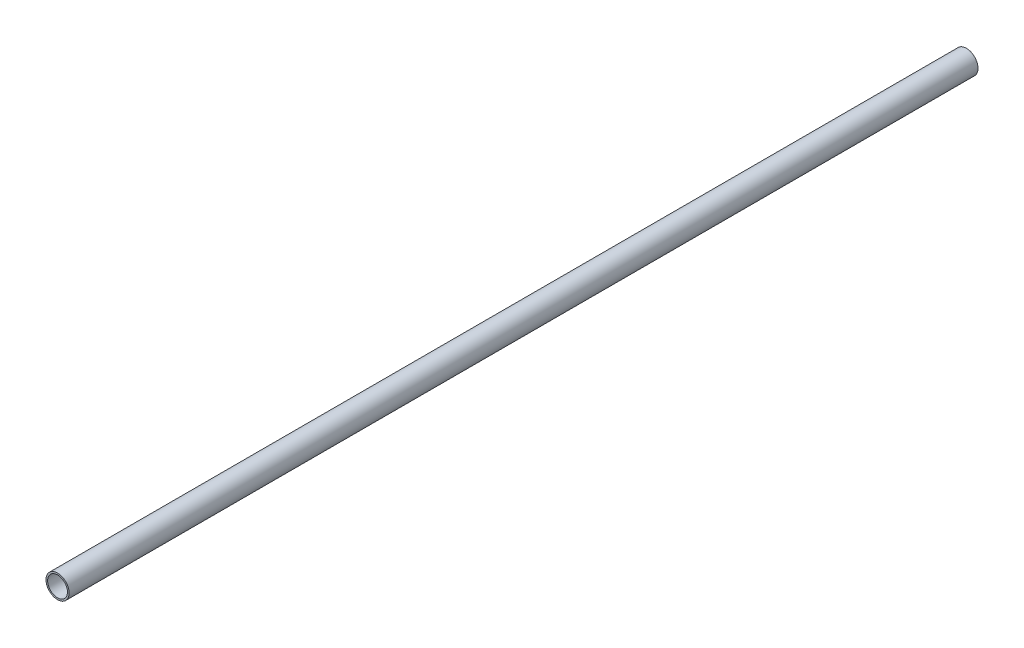
SolidWorks part; units mm, degrees
material "Carbon Fiber Tube - UD Approx"
ref_plane "Front Plane" through (0, 0, 0) normal (0, 0, 1) x (1, 0, 0)
ref_plane "Top Plane" through (0, 0, 0) normal (0, 1, 0) x (1, 0, 0)
ref_plane "Right Plane" through (0, 0, 0) normal (1, 0, 0) x (0, 0, -1)
sketch "Sketch1" plane through (0, 0, 0) normal (0, 0, 1) x (1, 0, 0)
  circle A0 centre (0, 0) radius 7
  circle A1 centre (0, 0) radius 6
  dimension "D1" = 14
  dimension "D2" = 12
extrude "Boss-Extrude1" add sketch "Sketch1" along normal blind 550
